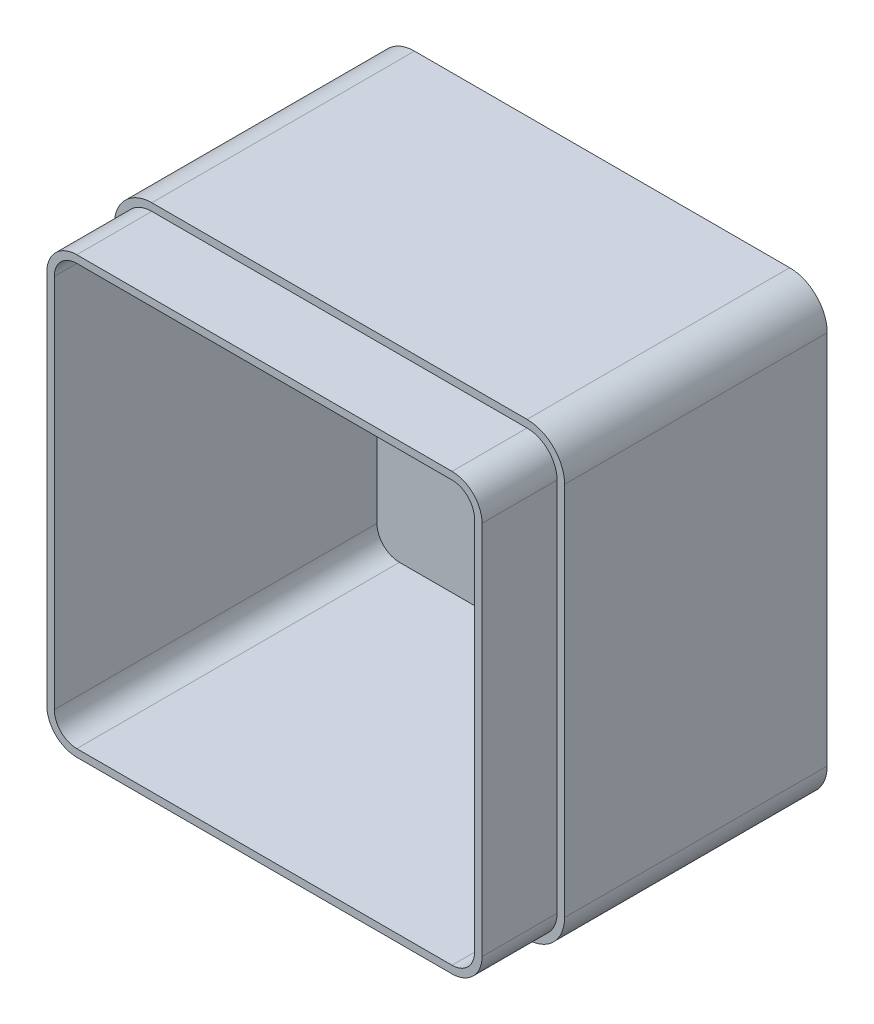
SolidWorks part; units mm, degrees
ref_plane "Front Plane" through (0, 0, 0) normal (0, 0, 1) x (1, 0, 0)
ref_plane "Top Plane" through (0, 0, 0) normal (0, 1, 0) x (1, 0, 0)
ref_plane "Right Plane" through (0, 0, 0) normal (1, 0, 0) x (0, 0, -1)
sketch "Sketch1" plane through (0, 0, 0) normal (0, 0, 1) x (1, 0, 0)
  line L1 (0, 0) -> (120, 0)
  line L2 (0, 0) -> (0, 120)
  line L3 (0, 120) -> (120, 120)
  line L4 (120, 0) -> (120, 120)
  dimension "D1" = 120
  dimension "D2" = 120
extrude "Boss-Extrude1" add sketch "Sketch1" along normal blind 90
fillet "Fillet1" radius 10 4 edges at (0, 0, 45) (120, 0, 45) (0, 120, 45) (120, 120, 45)
shell "Shell1" thickness 4
sketch "Sketch2" plane through (0, 0, 90) normal (0, 0, 1) x (1, 0, 0)
  line L1 (110, 118) -> (10, 118)
  line L2 (2, 110) -> (2, 10)
  line L3 (10, 2) -> (110, 2)
  line L4 (0, 110) -> (0, 10)
  line L5 (10, 0) -> (110, 0)
  line L6 (120, 10) -> (120, 110)
  line L7 (110, 120) -> (10, 120)
  line L8 (0, 110) -> (0, 10)
  line L9 (10, 0) -> (110, 0)
  line L10 (120, 10) -> (120, 110)
  line L11 (110, 120) -> (10, 120)
  line L12 (118, 10) -> (118, 110)
  arc A0 (10, 118) -> (2, 110) centre (10, 110) ccw
  arc A1 (2, 10) -> (10, 2) centre (10, 10) ccw
  arc A2 (110, 2) -> (118, 10) centre (110, 10) ccw
  arc A3 (118, 110) -> (110, 118) centre (110, 110) ccw
  arc A4 (0, 10) -> (10, 0) centre (10, 10) ccw
  arc A5 (110, 0) -> (120, 10) centre (110, 10) ccw
  arc A6 (120, 110) -> (110, 120) centre (110, 110) ccw
  arc A7 (10, 120) -> (0, 110) centre (10, 110) ccw
  arc A8 (0, 10) -> (10, 0) centre (10, 10) ccw
  arc A9 (110, 0) -> (120, 10) centre (110, 10) ccw
  arc A10 (120, 110) -> (110, 120) centre (110, 110) ccw
  arc A11 (10, 120) -> (0, 110) centre (10, 110) ccw
  dimension "D1" = 0
  dimension "D2" = 2
extrude "Cut-Extrude1" cut sketch "Sketch2" against normal blind 20
